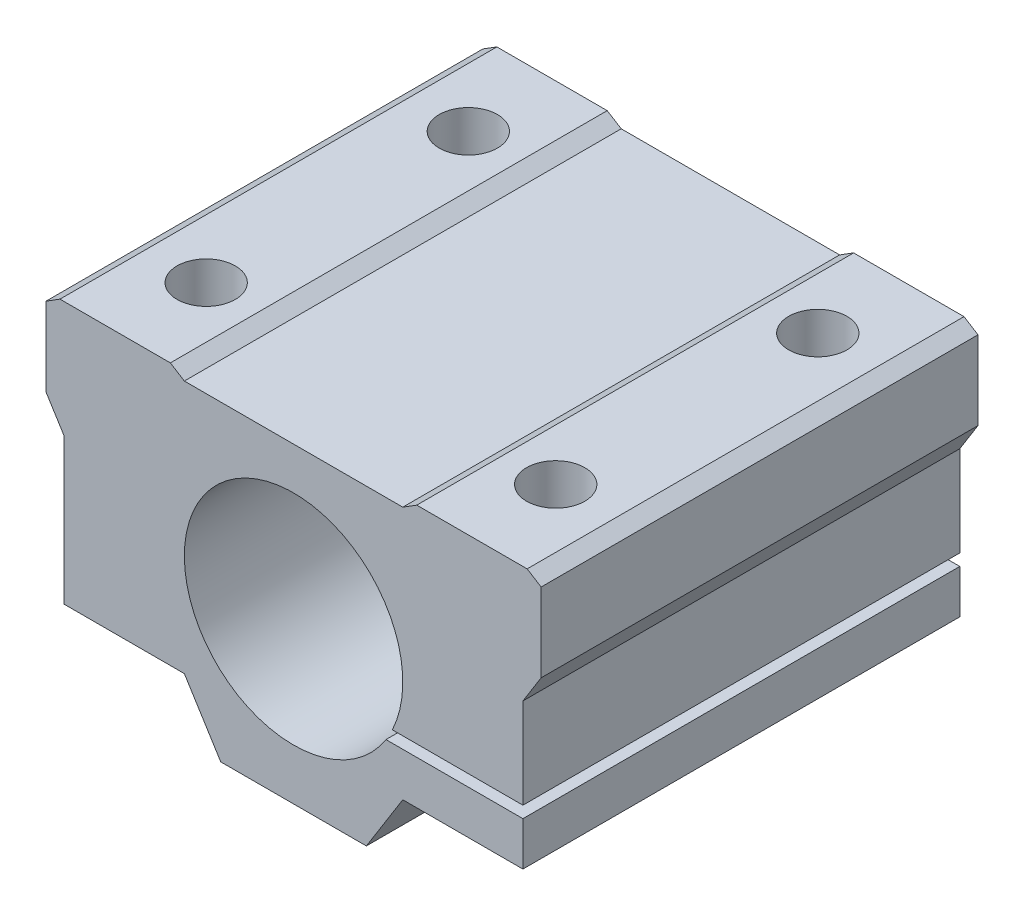
SolidWorks part; units mm, degrees
ref_plane "Alzado" through (0, 0, 0) normal (0, 0, 1) x (1, 0, 0)
ref_plane "Planta" through (0, 0, 0) normal (0, 1, 0) x (1, 0, 0)
ref_plane "Vista lateral" through (0, 0, 0) normal (1, 0, 0) x (0, 0, -1)
sketch "Croquis1" plane through (0, 0, 0) normal (0, 0, 1) x (1, 0, 0)
  line L0 (-5, -11) -> (5, -11)
  line L1 (5, -11) -> (7.5, -7)
  line L2 (7.5, -7) -> (15.75, -7)
  line L3 (15.75, -7) -> (15.75, 3)
  line L4 (15.75, 3) -> (17, 5)
  line L5 (17, 5) -> (17, 10.4)
  line L6 (17, 10.4) -> (16.04, 11)
  line L7 (16.04, 11) -> (8.46, 11)
  line L8 (8.46, 11) -> (7.5, 10.4)
  line L9 (7.5, 10.4) -> (-7.5, 10.4)
  line L10 (0, 10.4) -> (0, -11) construction
  line L11 (-5, -11) -> (-7.5, -7)
  line L12 (-7.5, -7) -> (-15.75, -7)
  line L13 (-15.75, -7) -> (-15.75, 3)
  line L14 (-15.75, 3) -> (-17, 5)
  line L15 (-17, 5) -> (-17, 10.4)
  line L16 (-17, 10.4) -> (-16.04, 11)
  line L17 (-16.04, 11) -> (-8.46, 11)
  line L18 (-8.46, 11) -> (-7.5, 10.4)
  circle A0 centre (0, 0) radius 7.5
  dimension "D1" = 15
  dimension "D2" = 22
  dimension "D3" = 11
  dimension "D4" = 8
  dimension "D5" = 18
  dimension "D6" = 17
  dimension "D7" = 6
  dimension "D8" = 7.5
  dimension "D9" = 15.75
  dimension "D10" = 21.4
extrude "Saliente-Extruir1" add sketch "Croquis1" along normal blind 30
sketch "Croquis2" plane through (0, 0, 30) normal (0, 0, 1) x (1, 0, 0)
  line L0 (7.5, -7) -> (15.75, -7) construction
  line L1 (17, -3.2) -> (5, -3.2)
  line L2 (17, -3.2) -> (17, -4)
  line L3 (17, -4) -> (5, -4)
  line L4 (5, -3.2) -> (5, -4)
  dimension "D1" = 3
  dimension "D2" = 0.8
  dimension "D3" = 12
  dimension "D4" = 5
extrude "Cortar-Extruir1" cut sketch "Croquis2" against normal through all
sketch "Croquis3" plane through (0, -7, 0) normal (0, -1, 0) x (1, 0, 0)
  line L0 (7.5, 30) -> (15.75, 30) construction
  line L1 (15.75, 30) -> (15.75, 0) construction
  circle A0 centre (11.625, 15) radius 1.05
  point P2 (11.625, 30)
  dimension "D1" = 2.1
  dimension "D2" = 15
  dimension "D3" = 4.125
extrude "Cortar-Extruir2" cut sketch "Croquis3" against normal blind 10
sketch "Croquis4" plane through (0, 11, 0) normal (0, 1, 0) x (1, 0, 0)
  line L0 (17, -30) -> (17, 0) construction
  line L2 (16.04, 0) -> (8.46, 0) construction
  line L3 (-17, -15) -> (17, -15) construction
  line L4 (-17, -30) -> (-17, 0) construction
  line L5 (0, 0) -> (0, -30) construction
  line L6 (7.5, 0) -> (-7.5, 0) construction
  line L7 (7.5, -30) -> (-7.5, -30) construction
  circle A0 centre (12, -6) radius 1.7
  circle A1 centre (-12, -6) radius 1.7
  circle A2 centre (-12, -24) radius 1.7
  circle A3 centre (12, -24) radius 1.7
  dimension "D1" = 3.4
  dimension "D2" = 5
  dimension "D3" = 6
extrude "Cortar-Extruir3" cut sketch "Croquis4" against normal through all
sketch "Croquis5" plane through (0, 11, 0) normal (0, 1, 0) x (1, 0, 0)
  line L0 (0, 0) -> (0, -30) construction
  line L1 (7.5, -30) -> (-7.5, -30) construction
  line L2 (-17, -15) -> (17, -15) construction
  line L3 (-17, -30) -> (-17, 0) construction
  line L4 (17, -30) -> (17, 0) construction
  circle A0 centre (12, -6) radius 2
  circle A1 centre (-12, -6) radius 2
  circle A2 centre (-12, -24) radius 2
  circle A3 centre (12, -24) radius 2
  dimension "D1" = 4
extrude "Cortar-Extruir4" cut sketch "Croquis5" against normal blind 8
